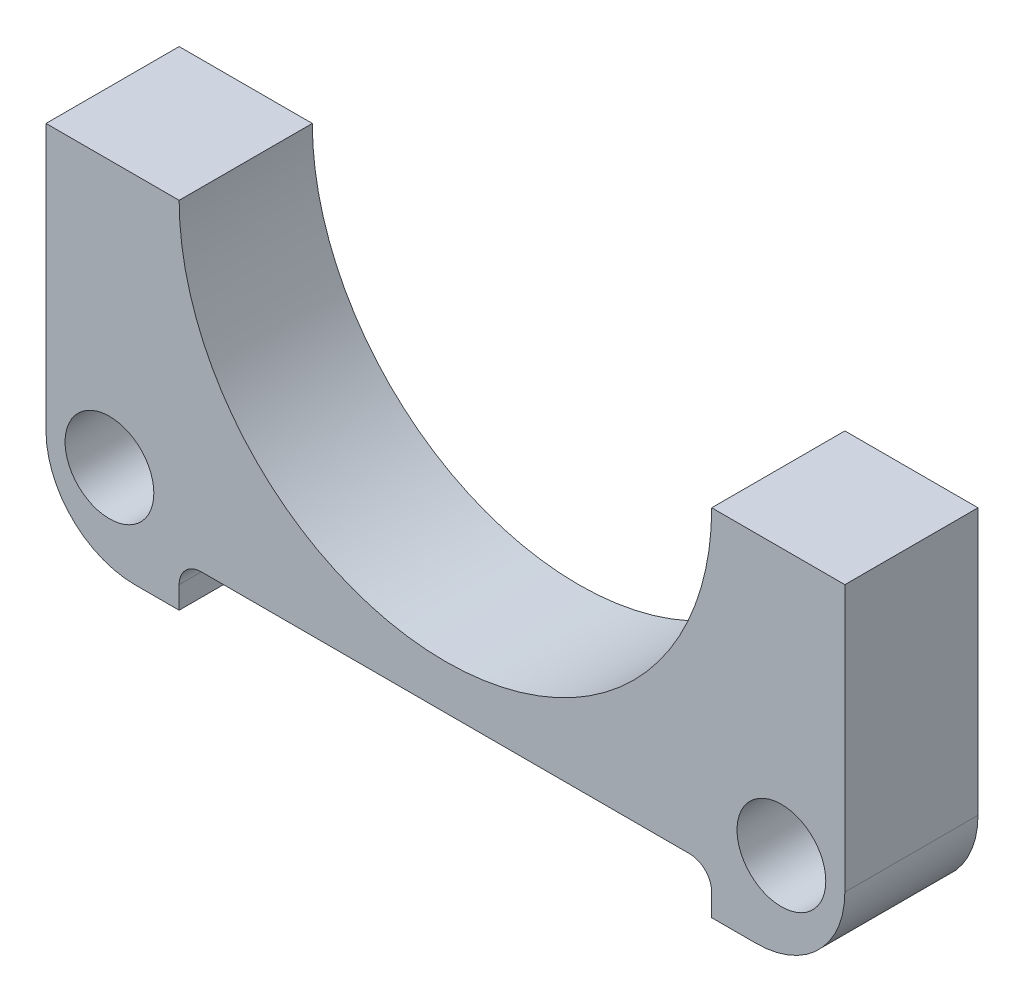
SolidWorks part; units mm, degrees
ref_plane "Front Plane" through (0, 0, 0) normal (0, 0, 1) x (1, 0, 0)
ref_plane "Top Plane" through (0, 0, 0) normal (0, 1, 0) x (1, 0, 0)
ref_plane "Right Plane" through (0, 0, 0) normal (1, 0, 0) x (0, 0, -1)
sketch "Sketch1" plane through (0, 0, 0) normal (0, 0, 1) x (1, 0, 0)
  line L0 (60, 40) -> (90, 40)
  line L1 (-90, 40) -> (-60, 40)
  line L2 (-90, 40) -> (-90, -20)
  line L3 (-70, -40) -> (-60, -40)
  line L4 (90, 40) -> (90, -20)
  line L5 (-90, 40) -> (90, -40) construction
  line L6 (-90, -40) -> (90, 40) construction
  line L7 (-55, -30) -> (55, -30)
  line L8 (-60, -35) -> (-60, -40)
  line L10 (60, -35) -> (60, -40)
  line L11 (-60, -30) -> (-20.2252, -36.7695) construction
  line L13 (60, -40) -> (70, -40)
  arc A0 (-60, 40) -> (60, 40) centre (0, 40) ccw
  circle A1 centre (-75.7021, -20) radius 10
  circle A2 centre (75.7, -20) radius 10
  arc A3 (-90, -20) -> (-70, -40) centre (-70, -20) ccw
  arc A4 (70, -40) -> (90, -20) centre (70, -20) ccw
  arc A5 (55, -30) -> (60, -35) centre (55, -35) cw
  arc A6 (-55, -30) -> (-60, -35) centre (-55, -35) ccw
  point P0 (0, 0)
  point P9 (0, -40.2118)
  point P17 (0, 0)
  point P18 (0, 0)
  point P19 (0, 0)
  point P20 (0, 0)
  point P21 (0, 0)
  dimension "D1" = 20
  dimension "D3" = 75.7021
  dimension "D7" = 120
  dimension "D9" = 20
  dimension "D10" = 20
  dimension "D11" = 20
  dimension "D14" = 5
  dimension "D2" = 90
  dimension "D4" = 75.7
  dimension "D5" = 180
  dimension "D6" = 30
  dimension "D8" = 80
  dimension "D12" = 20
  dimension "D13" = 20
  dimension "D15" = 10
extrude "Boss-Extrude1" add sketch "Sketch1" along normal mid plane 30
